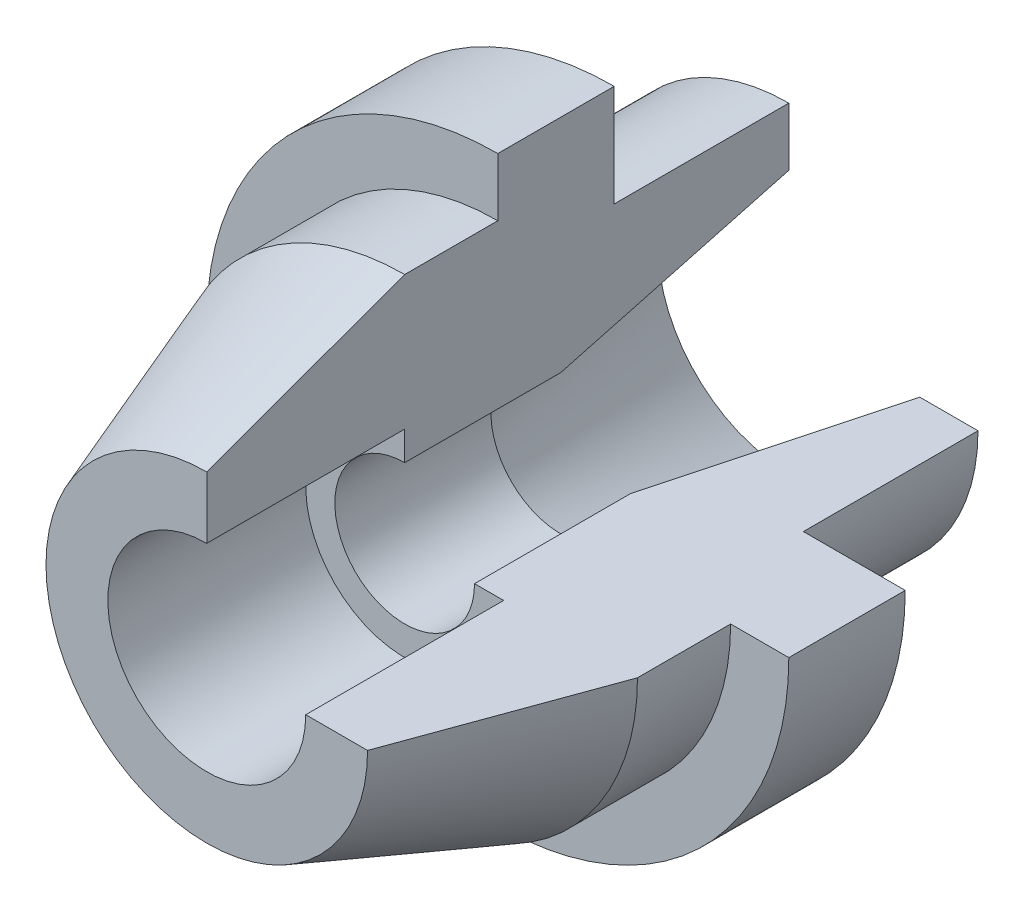
SolidWorks part; units mm, degrees
ref_plane "Front Plane" through (0, 0, 0) normal (0, 0, 1) x (1, 0, 0)
ref_plane "Top Plane" through (0, 0, 0) normal (0, 1, 0) x (1, 0, 0)
ref_plane "Right Plane" through (0, 0, 0) normal (1, 0, 0) x (0, 0, -1)
sketch "Sketch1" plane through (0, 0, 0) normal (1, 0, 0) x (0, 0, -1)
  line L0 (0, 0) -> (118.0761, 0) construction
  line L1 (0, 17) -> (0, 27.625)
  line L2 (0, 27.625) -> (34, 40)
  line L3 (34, 40) -> (50, 40)
  line L4 (50, 40) -> (50, 50)
  line L5 (50, 50) -> (70, 50)
  line L6 (70, 50) -> (70, 32.5)
  line L7 (70, 32.5) -> (100, 32.5)
  line L8 (100, 32.5) -> (100, 22.5)
  line L9 (100, 22.5) -> (60.8135, 12)
  line L10 (60.8135, 12) -> (34, 12)
  line L11 (34, 12) -> (34, 17)
  line L12 (34, 17) -> (0, 17)
  point P8 (80.1957, 12.9348)
  point P16 (0, 0)
  point P17 (0, 0)
  dimension "D1" = 34
  dimension "D2" = 24
  dimension "D3" = 15
  dimension "D4" = 65
  dimension "D5" = 100
  dimension "D6" = 34
  dimension "D7" = 70
  dimension "D8" = 20
  dimension "D9" = 10
  dimension "D10" = 100
  dimension "D11" = 80
  dimension "D12" = 30
revolve "Revolve1" add sketch "Sketch1" angle 270 about L0
